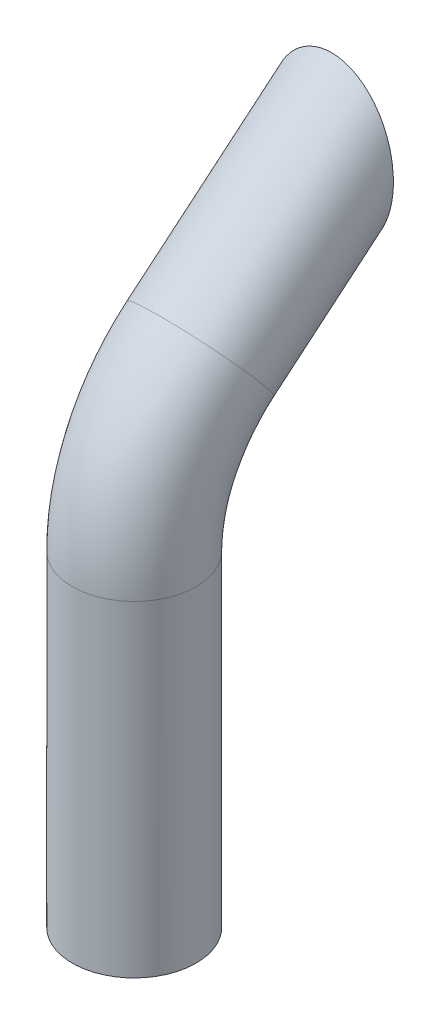
SolidWorks part; units mm, degrees
ref_plane "Front Plane" through (0, 0, 0) normal (0, 0, 1) x (1, 0, 0)
ref_plane "Top Plane" through (0, 0, 0) normal (0, 1, 0) x (1, 0, 0)
ref_plane "Right Plane" through (0, 0, 0) normal (1, 0, 0) x (0, 0, -1)
sketch "Sketch1" plane through (0, 0, 0) normal (1, 0, 0) x (0, 0, -1)
  line L0 (0, 0) -> (-82.7576, -69.4418)
  line L1 (-114.9067, -138.3858) -> (-114.9067, -296.4181)
  arc A0 (-82.7576, -69.4418) -> (-114.9067, -138.3858) centre (-24.9067, -138.3858) ccw
  point P6 (-114.9067, -96.4181)
  dimension "D4" = 90
  dimension "D1" = 150
  dimension "D2" = 200
  dimension "D3" = 130
ref_plane "Plane1" through (0, 0, 0) normal (0, -0.6428, 0.766) x (1, 0, 0)
sketch "Sketch2" plane through (0, 0, 0) normal (0, -0.6428, 0.766) x (1, 0, 0)
  circle A0 centre (0, 0) radius 30
  dimension "D1" = 60
sweep "Sweep-Thin1" add profiles "Sketch2" path "Sketch1" parameters "D1"=3
sketch "Sketch4" plane through (0, 0, 0) normal (1, 0, 0) x (0, 0, -1)
  line L1 (57.8509, -68.944) -> (-19.2836, -68.944)
  line L2 (57.8509, -68.944) -> (57.8509, 22.9813)
  line L3 (57.8509, 22.9813) -> (-19.2836, 22.9813)
  line L4 (-19.2836, -68.944) -> (-19.2836, 22.9813)
  line L5 (57.8509, -68.944) -> (-19.2836, 22.9813) construction
  line L6 (57.8509, 22.9813) -> (-19.2836, -68.944) construction
  point P0 (19.2836, -22.9813)
extrude "Cut-Extrude1" cut sketch "Sketch4" against normal mid plane 90
